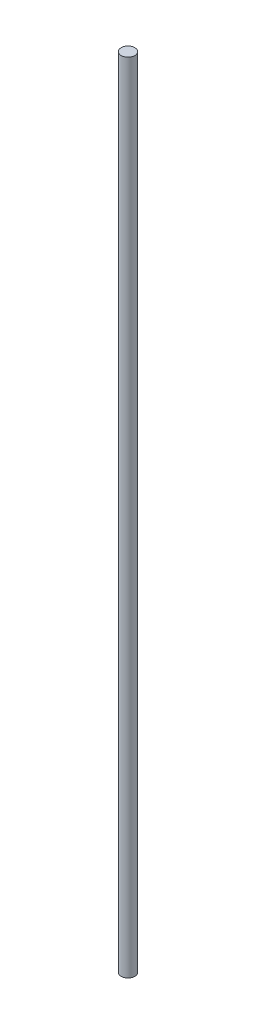
SolidWorks part; units mm, degrees
ref_plane "Front Plane" through (0, 0, 0) normal (0, 0, 1) x (1, 0, 0)
ref_plane "Top Plane" through (0, 0, 0) normal (0, 1, 0) x (1, 0, 0)
ref_plane "Right Plane" through (0, 0, 0) normal (1, 0, 0) x (0, 0, -1)
sketch "Sketch1" plane through (0, 0, 0) normal (0, 1, 0) x (1, 0, 0)
  circle A0 centre (0, 0) radius 3
  dimension "D1" = 6
extrude "Boss-Extrude1" add sketch "Sketch1" along normal blind 350
